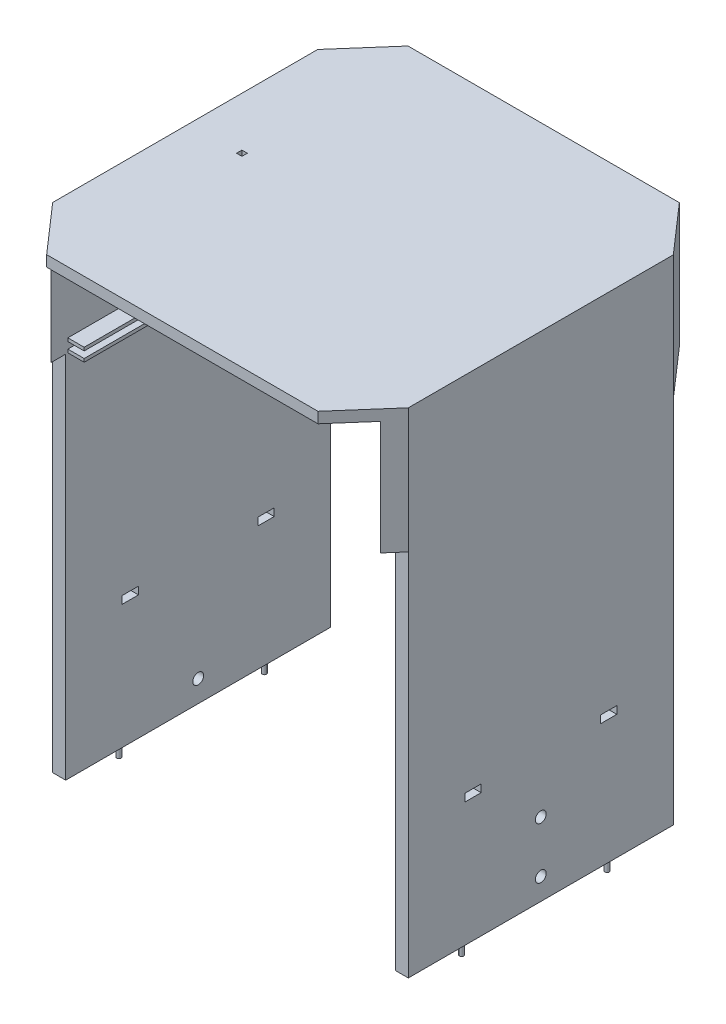
SolidWorks part; units mm, degrees
ref_plane "Plan de face" through (0, 0, 0) normal (0, 0, 1) x (1, 0, 0)
ref_plane "Plan de dessus" through (0, 0, 0) normal (0, 1, 0) x (1, 0, 0)
ref_plane "Plan de droite" through (0, 0, 0) normal (1, 0, 0) x (0, 0, -1)
sketch "Esquisse1" plane through (0, 0, 0) normal (0, 1, 0) x (1, 0, 0)
  line L0 (-125, 166.4835) -> (125, 166.4835)
  line L1 (-125, -166.4835) -> (125, -166.4835)
  line L2 (-163.8462, 122.0879) -> (-163.8462, -122.0879)
  line L3 (-163.8462, 122.0879) -> (-125, 166.4835)
  line L4 (-163.8462, -122.0879) -> (-125, -166.4835)
  line L5 (163.8462, -122.0879) -> (125, -166.4835)
  line L6 (163.8462, 122.0879) -> (163.8462, -122.0879)
  line L7 (163.8462, 122.0879) -> (125, 166.4835)
  point P3 (0, 166.4835)
  point P8 (-163.8462, 0)
extrude "Boss.-Extru.1" add sketch "Esquisse1" along normal blind 5
sketch "Esquisse3" plane through (0, 0, 0) normal (0, -1, 0) x (1, 0, 0)
  line L0 (-151.8462, 122.0879) -> (-151.8462, -122.0879)
  line L1 (-151.8462, 122.0879) -> (-163.8462, 122.0879)
  line L2 (-163.8462, 122.0879) -> (-163.8462, -122.0879)
  line L3 (-163.8462, -122.0879) -> (-151.8462, -122.0879)
  line L8 (0, -211.2715) -> (0, 213.8837) construction
  line L9 (163.8462, -122.0879) -> (151.8462, -122.0879)
  line L10 (151.8462, 122.0879) -> (163.8462, 122.0879)
  line L11 (151.8462, 122.0879) -> (151.8462, -122.0879)
  line L12 (163.8462, 122.0879) -> (163.8462, -122.0879)
extrude "Boss.-Extru.3" add sketch "Esquisse3" along normal blind 450
sketch "Esquisse4" plane through (0, -450, 0) normal (0, -1, 0) x (1, 0, 0)
  circle A2 centre (-157.8462, 67) radius 2
  circle A7 centre (-157.8462, -67) radius 2
  circle A8 centre (157.8462, -67) radius 2
  circle A9 centre (157.8462, 67) radius 2
extrude "Boss.-Extru.6" add sketch "Esquisse4" along normal blind 12
sketch "Esquisse8" plane through (-163.8462, 0, 0) normal (-1, 0, 0) x (0, 0, 1)
  line L0 (122.0879, -450) -> (-122.0879, -450) construction
  circle A0 centre (0, -430) radius 5
  dimension "D1" = 20
extrude "Enlèv. mat.-Extru.2" cut sketch "Esquisse8" against normal blind 416
ref_plane "Plan2" through (0, -110, 0) normal (0, -1, 0) x (-1, 0, 0)
sketch "Esquisse10" plane through (0, -110, 0) normal (0, -1, 0) x (-1, 0, 0)
  line L0 (-163.8462, 122.0879) -> (-125, 166.4835)
  line L1 (-125, 166.4835) -> (125, 166.4835)
  line L2 (125, 166.4835) -> (163.8462, 122.0879)
  line L3 (163.8462, 122.0879) -> (163.8462, -122.0879)
  line L4 (163.8462, -122.0879) -> (125, -166.4835)
  line L5 (125, -166.4835) -> (-125, -166.4835)
  line L6 (-125, -166.4835) -> (-163.8462, -122.0879)
  line L7 (-163.8462, -122.0879) -> (-163.8462, 122.0879)
  line L8 (-151.8462, -122.0879) -> (-151.8462, 122.0879)
  line L9 (-151.8462, 122.0879) -> (-125.4906, 152.2085)
  line L10 (-125.4906, 152.2085) -> (125.4906, 152.2085)
  line L13 (-125.4906, -152.2085) -> (125.4906, -152.2085)
  line L14 (-151.8462, -122.0879) -> (-125.4906, -152.2085)
  line L15 (151.8462, -122.0879) -> (125.4906, -152.2085)
  line L16 (151.8462, 122.0879) -> (125.4906, 152.2085)
  line L17 (151.8462, -122.0879) -> (151.8462, 122.0879)
extrude "Boss.-Extru.7" add sketch "Esquisse10" against normal up to surface (110 mm away) up to face at (0, 0, 0)
sketch "Esquisse11" plane through (0, 0, 152.2085) normal (0, 0, -1) x (-1, 0, 0)
  line L2 (-151.8462, -450) -> (-151.8462, -110) construction
  line L6 (-151.8462, -119.1987) -> (-151.8462, -5)
  line L7 (151.8462, -5) -> (151.8462, -119.1987)
  line L8 (151.8462, -450) -> (151.8462, -110) construction
  line L11 (-151.8462, -119.1987) -> (151.8462, -119.1987)
  line L12 (-151.8462, -5) -> (151.8462, -5)
extrude "Enlèv. mat.-Extru.6" cut sketch "Esquisse11" along normal blind 148 and the other way blind 101
sketch "Esquisse12" plane through (151.8462, 0, 0) normal (-1, 0, 0) x (0, 0, 1)
  line L2 (-70, -335.6649) -> (70, -335.6649)
  line L3 (-70, -335.6649) -> (-70, -328.6649)
  line L4 (-70, -328.6649) -> (70, -328.6649)
  line L5 (70, -335.6649) -> (70, -328.6649)
  point P3 (0, -332.1649)
extrude "Enlèv. mat.-Extru.8" cut sketch "Esquisse12" against normal blind 666 and the other way blind 666
ref_plane "Plan3" through (-163.8462, -335.6649, 70) normal (0, 1, 0) x (1, 0, 0)
sketch "Esquisse16" plane through (-151.8462, 0, 0) normal (1, 0, 0) x (0, 0, -1)
  line L5 (0, -146.9867) -> (0, 85.2756)
  line L6 (-122.0879, -110) -> (-120.0879, -110)
  line L7 (-180.2308, -110) -> (180.2308, -110) construction
  line L8 (-120.0879, -110) -> (-120.0879, -107)
  line L9 (-120.0879, -107) -> (122.0879, -107)
  line L10 (122.0879, 5) -> (122.0879, -110) construction
  line L11 (122.0879, -107) -> (122.0879, -110)
  line L12 (-120.0879, -110) -> (122.0879, -110)
  line L15 (122.0879, -101) -> (122.0879, -98)
  line L16 (-120.0879, -98) -> (-120.0879, -101)
  line L17 (-120.0879, -98) -> (122.0879, -98)
  line L18 (-120.0879, -101) -> (122.0879, -101)
extrude "Boss.-Extru.8" add sketch "Esquisse16" along normal blind 15 contours L12 L11 L9 L8 | L18 L15 L17 L16
sketch "Esquisse17" plane through (-136.8462, 0, 0) normal (1, 0, 0) x (0, 0, -1)
  line L0 (122.0879, -98) -> (122.0879, -110)
  line L1 (122.0879, 5) -> (122.0879, -110) construction
  line L2 (122.0879, -110) -> (119.0879, -110)
  line L3 (-180.2308, -110) -> (180.2308, -110) construction
  line L4 (119.0879, -110) -> (119.0879, -98)
  line L6 (-120.0879, -98) -> (122.0879, -98) construction
  line L7 (119.0879, -98) -> (122.0879, -98)
extrude "Boss.-Extru.11" add sketch "Esquisse17" against normal up to surface (15 mm away) up to face at (-151.8462, -430, 5)
mirror "Symétrie2" about plane through (0, 0, 0) normal (1, 0, 0) of "Boss.-Extru.8"
sketch "Esquisse19" plane through (0, 0, -122.0879) normal (0, 0, -1) x (-1, 0, 0)
  line L0 (-151.8462, -110) -> (-136.8462, -110)
  line L1 (-180.2308, -110) -> (180.2308, -110) construction
  line L2 (-136.8462, -110) -> (-136.8462, -98)
  line L3 (-136.8462, -98) -> (-151.8462, -98)
  line L4 (-151.8462, -98) -> (-151.8462, -110)
extrude "Boss.-Extru.12" add sketch "Esquisse19" against normal blind 3
sketch "Esquisse20" plane through (0, 0, 0) normal (0, -1, 0) x (1, 0, 0)
  point P0 (0, 0)
sketch "Esquisse23" plane through (-151.8462, 0, 0) normal (1, 0, 0) x (0, 0, -1)
  line L2 (0, -335.6649) -> (0, -450)
  line L3 (122.0879, -450) -> (-122.0879, -450) construction
  line L4 (-70, -335.6649) -> (70, -335.6649) construction
  line L5 (-55, -335.6649) -> (-55, -328.6649)
  line L6 (70, -328.6649) -> (-70, -328.6649) construction
  line L8 (55, -335.6649) -> (55, -328.6649)
  line L9 (55, -328.6649) -> (-55, -328.6649)
  line L10 (-55, -335.6649) -> (55, -335.6649)
  point P5 (0, -335.6649)
extrude "Boss.-Extru.13" add sketch "Esquisse23" against normal up to surface (12 mm away) contours L9 L5 L10 L8 up to face at (-163.8462, -430, 5)
sketch "Esquisse24" plane through (163.8462, 0, 0) normal (1, 0, 0) x (0, 0, -1)
  line L0 (-55, -328.6649) -> (55, -328.6649)
  line L2 (70, -328.6649) -> (-70, -328.6649) construction
  line L3 (-55, -328.6649) -> (-55, -335.6649)
  line L4 (55, -328.6649) -> (55, -335.6649)
  line L5 (55, -335.6649) -> (-55, -335.6649)
extrude "Boss.-Extru.14" add sketch "Esquisse24" against normal up to surface (12 mm away) up to face at (151.8462, -332.1649, 0)
sketch "Esquisse27" plane through (151.8462, 0, 0) normal (-1, 0, 0) x (0, 0, 1)
  line L1 (122.0879, -450) -> (-122.0879, -450) construction
  line L7 (-87.5015, -450) -> (-87.5015, -112)
  line L8 (-87.5015, -112) -> (-77.5015, -112)
  line L9 (-77.5015, -112) -> (-77.5015, -450)
  line L10 (-87.5015, -450) -> (-77.5015, -450)
extrude "Boss.-Extru.16" add sketch "Esquisse27" along normal up to surface (303.6923 mm away) up to face at (-151.8462, -332.1649, -62.5)
mirror "Symétrie4" about plane through (0, 0, 0) normal (0, 0, 1) of "Boss.-Extru.16"
sketch "Esquisse28" plane through (0, 5, 0) normal (0, 1, 0) x (1, 0, 0)
  line L1 (-118.4507, 6.9163) -> (-113.4507, 6.9163)
  line L2 (-118.4507, 6.9163) -> (-118.4507, 1.9163)
  line L3 (-118.4507, 1.9163) -> (-113.4507, 1.9163)
  line L4 (-113.4507, 6.9163) -> (-113.4507, 1.9163)
  line L5 (-118.4507, 6.9163) -> (-113.4507, 1.9163) construction
  line L6 (-118.4507, 1.9163) -> (-113.4507, 6.9163) construction
  point P0 (-115.9507, 4.4163)
extrude "Enlèv. mat.-Extru.9" cut sketch "Esquisse28" against normal blind 15
sketch "Esquisse29" plane through (163.8462, 0, 0) normal (1, 0, 0) x (0, 0, -1)
  circle A1 centre (0, -382.55) radius 5
extrude "Enlèv. mat.-Extru.10" cut sketch "Esquisse29" against normal blind 38
sketch "Esquisse30" plane through (0, -450, 0) normal (0, -1, 0) x (1, 0, 0)
  line L0 (-151.8462, 87.5015) -> (-151.8462, 77.5015)
  line L1 (-151.8462, 77.5015) -> (151.8462, 77.5015)
  line L2 (-151.8462, 87.5015) -> (151.8462, 87.5015)
  line L3 (151.8462, 87.5015) -> (151.8462, 77.5015)
extrude "Enlèv. mat.-Extru.11" cut sketch "Esquisse30" against normal up to surface (340 mm away) up to face at (-144.3462, -110, -1)
sketch "Esquisse31" plane through (0, -450, 0) normal (0, -1, 0) x (1, 0, 0)
  line L0 (-151.8462, -77.5015) -> (151.8462, -77.5015)
  line L1 (151.8462, -77.5015) -> (151.8462, -87.5015)
  line L2 (151.8462, -87.5015) -> (-151.8462, -87.5015)
  line L3 (-151.8462, -87.5015) -> (-151.8462, -77.5015)
extrude "Enlèv. mat.-Extru.12" cut sketch "Esquisse31" against normal up to surface (338 mm away) up to face at (0, -112, -82.5015)
sketch "Esquisse33" plane through (0, -110, 0) normal (0, -1, 0) x (-1, 0, 0)
  line L2 (125, 166.4835) -> (-125, 166.4835) construction
  line L3 (-21.9574, 185.3231) -> (21.9574, 185.3231)
  line L6 (-21.9574, 185.3231) -> (-34.4003, 166.4835)
  line L7 (0, 177.1752) -> (0, 194.0577) construction
  line L8 (21.9574, 185.3231) -> (34.4003, 166.4835)
  line L9 (-34.4003, 166.4835) -> (34.4003, 166.4835)
  point P10 (0, 185.3231)
extrude "Boss.-Extru.18" add sketch "Esquisse33" against normal blind 10
sketch "Esquisse34" plane through (0, -110, 0) normal (0, -1, 0) x (1, 0, 0)
  circle A0 centre (0, -177.983) radius 3.6443
  point P10 (1.4396, -181.331)
extrude "Boss.-Extru.19" add sketch "Esquisse34" along normal blind 340
sketch "Esquisse35" plane through (0, -450, 0) normal (0, -1, 0) x (1, 0, 0)
  circle A4 centre (0, -177.983) radius 3.6443
